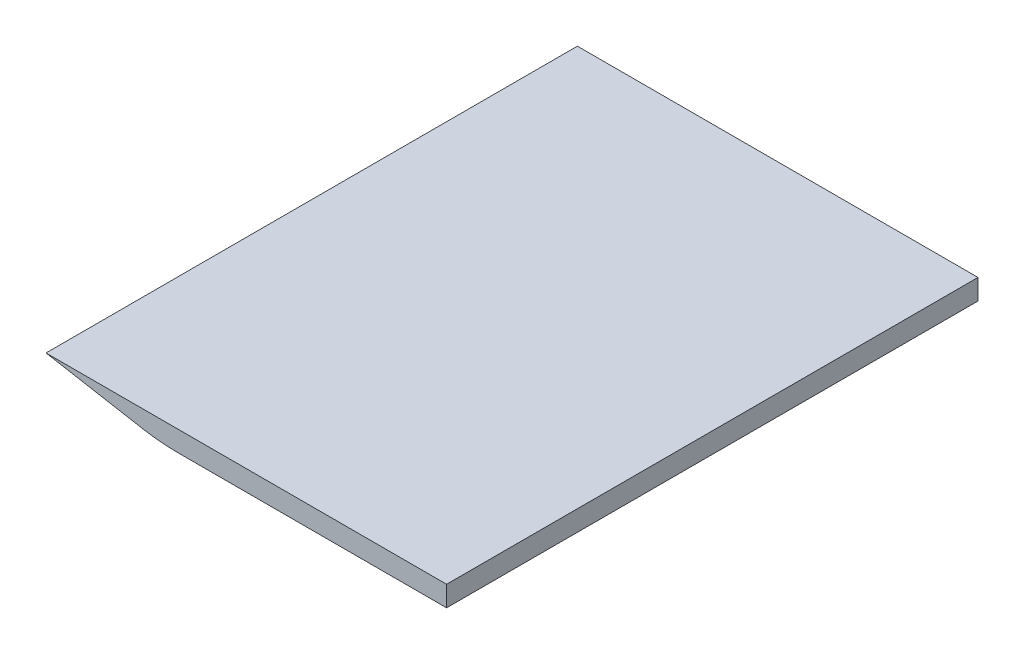
SolidWorks part; units mm, degrees
ref_plane "Front Plane" through (0, 0, 0) normal (0, 0, 1) x (1, 0, 0)
ref_plane "Top Plane" through (0, 0, 0) normal (0, 1, 0) x (1, 0, 0)
ref_plane "Right Plane" through (0, 0, 0) normal (1, 0, 0) x (0, 0, -1)
sketch "Sketch1" plane through (0, 0, 0) normal (0, 0, 1) x (1, 0, 0)
  line L0 (0, 0) -> (98, 0)
  line L1 (98, 0) -> (98, -5)
  line L2 (98, -5) -> (28, -5)
  line L3 (28, -5) -> (0, 0)
  dimension "D1" = 70
  dimension "D2" = 28
  dimension "D3" = 5
extrude "Boss-Extrude1" add sketch "Sketch1" along normal blind 130
fillet "Fillet1" radius 50 1 edges at (28, -5, 65)
